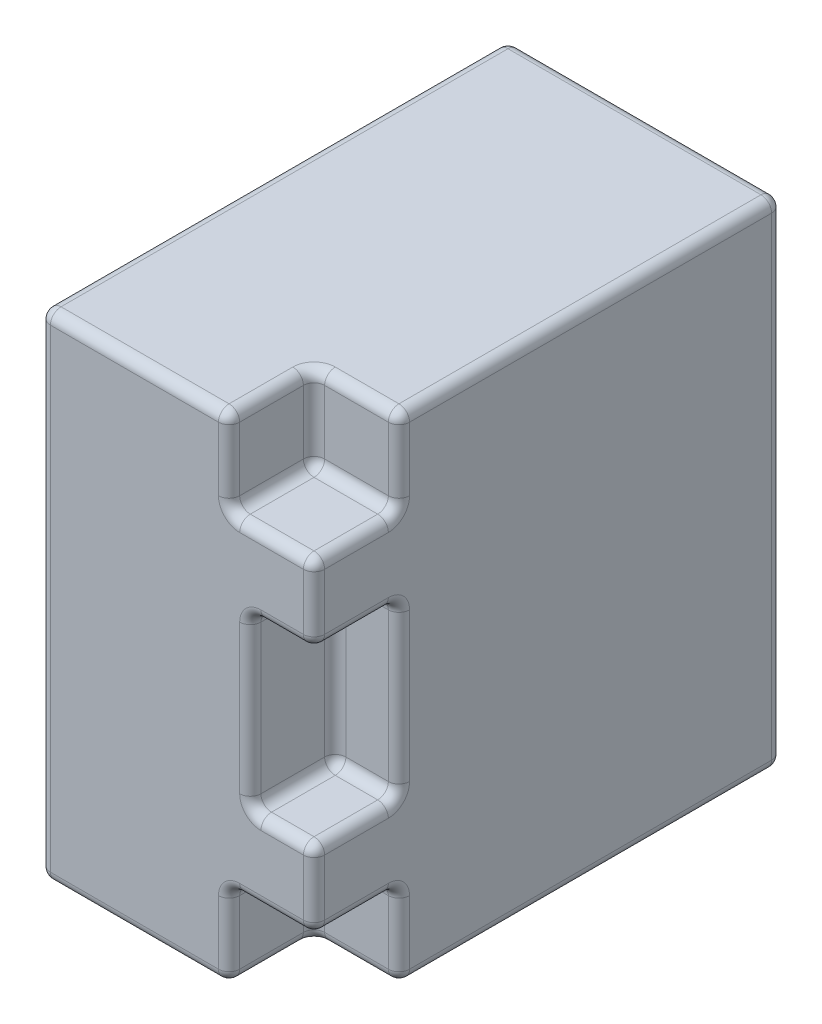
SolidWorks part; units mm, degrees
material "ABS"
ref_plane "X-Y Datum" through (0, 0, 0) normal (0, 0, 1) x (1, 0, 0)
ref_plane "X-Z Datum" through (0, 0, 0) normal (0, 1, 0) x (1, 0, 0)
ref_plane "Y-Z Datum" through (0, 0, 0) normal (1, 0, 0) x (0, 0, -1)
sketch "Sketch1" plane through (0, 0, 0) normal (0, 0, 1) x (1, 0, 0)
  line L1 (41, -74) -> (-41, -74)
  line L2 (41, -74) -> (41, 74)
  line L3 (41, 74) -> (-41, 74)
  line L4 (-41, -74) -> (-41, 74)
  line L5 (41, -74) -> (-41, 74) construction
  line L6 (41, 74) -> (-41, -74) construction
  point P0 (0, 0)
  dimension "D1" = 148
  dimension "D2" = 82
extrude "Boss-Extrude1" add sketch "Sketch1" along normal blind 140
sketch "Sketch2" plane through (0, 0, 140) normal (0, 0, 1) x (1, 0, 0)
  line L0 (41, -74) -> (41, 74) construction
  line L1 (41, -74) -> (15.6, -74)
  line L2 (41, -74) -> (41, -48.6)
  line L3 (41, -48.6) -> (15.6, -48.6)
  line L4 (15.6, -74) -> (15.6, -48.6)
  line L5 (41, 74) -> (15.6, 74)
  line L6 (41, 74) -> (41, 48.6)
  line L7 (41, 48.6) -> (15.6, 48.6)
  line L8 (15.6, 74) -> (15.6, 48.6)
  line L9 (41, -25.4) -> (21.95, -25.4)
  line L10 (41, -25.4) -> (41, 25.4)
  line L11 (41, 25.4) -> (21.95, 25.4)
  line L12 (21.95, -25.4) -> (21.95, 25.4)
  point P16 (41, 0)
  point P17 (41, 0)
  dimension "D1" = 25.4
  dimension "D2" = 25.4
  dimension "D3" = 19.05
  dimension "D4" = 50.8
extrude "Cut-Extrude1" cut sketch "Sketch2" against normal blind 25.4
fillet "Fillet1" radius 3.175 42 edges at (-41, 0, 0) (-41, 74, 70) (0, 74, 0) (28.3, 74, 114.6) (0, -74, 0) (-41, -74, 70) (28.3, -74, 114.6) (41, -25.4, 127.3) (41, 25.4, 127.3) (41, 61.3, 114.6) (41, 74, 57.3) (41, 0, 0) (41, -74, 57.3) (41, -61.3, 114.6) (-12.7, -74, 140) (-41, 0, 140) (-12.7, 74, 140) (41, 37, 140) (31.475, 25.4, 140) (31.475, -25.4, 140) (41, -37, 140) (15.6, 74, 127.3) (15.6, 61.3, 114.6) (15.6, 61.3, 140) (15.6, 48.6, 127.3) (28.3, 48.6, 114.6) (41, 48.6, 127.3) (28.3, 48.6, 140) (31.475, -25.4, 114.6) (31.475, 25.4, 114.6) (41, 0, 114.6) (21.95, 25.4, 127.3) (21.95, 0, 114.6) (21.95, -25.4, 127.3) (21.95, 0, 140) (41, -48.6, 127.3) (28.3, -48.6, 114.6) (28.3, -48.6, 140) (15.6, -48.6, 127.3) (15.6, -61.3, 114.6) (15.6, -74, 127.3) (15.6, -61.3, 140)
